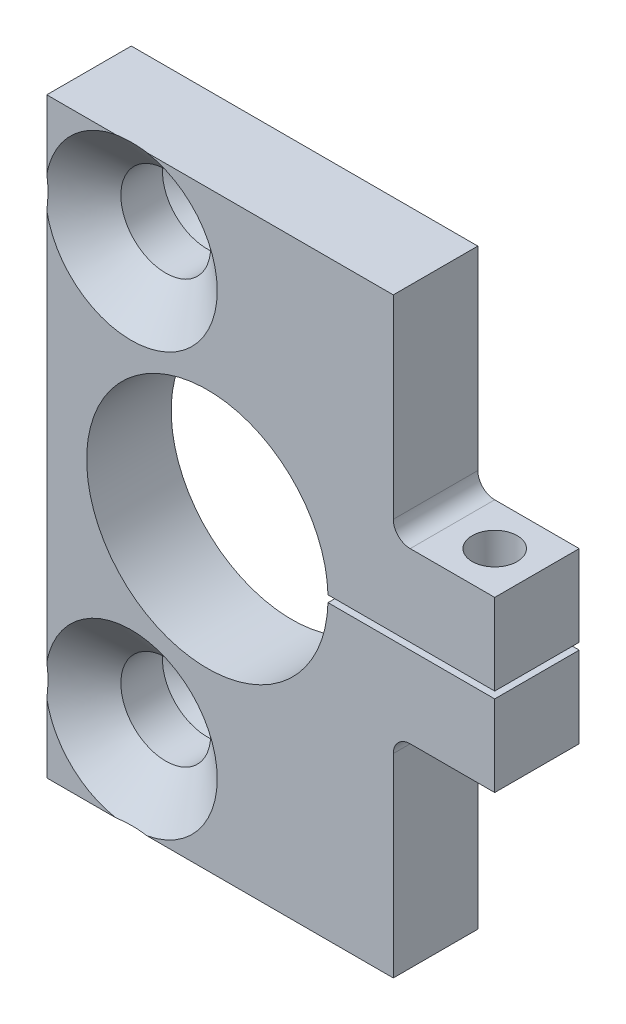
SolidWorks part; units mm, degrees
material "6061-T6 (SS)"
ref_plane "Front Plane" through (0, 0, 0) normal (0, 0, 1) x (1, 0, 0)
ref_plane "Top Plane" through (0, 0, 0) normal (0, 1, 0) x (1, 0, 0)
ref_plane "Right Plane" through (0, 0, 0) normal (1, 0, 0) x (0, 0, -1)
sketch "Sketch1" plane through (0, 0, 0) normal (0, 0, 1) x (1, 0, 0)
  line L1 (-33.655, -44.45) -> (33.655, -44.45)
  line L2 (-33.655, -44.45) -> (-33.655, 44.45)
  line L3 (-33.655, 44.45) -> (33.655, 44.45)
  line L4 (33.655, -44.45) -> (33.655, 44.45)
  line L5 (-33.655, -44.45) -> (33.655, 44.45) construction
  line L6 (-33.655, 44.45) -> (33.655, -44.45) construction
  point P0 (0, 0)
  dimension "D1" = 67.31
  dimension "D2" = 88.9
extrude "Extrude1" add sketch "Sketch1" along normal blind 12.7
sketch "Sketch2" plane through (0, 0, 12.7) normal (0, 0, 1) x (1, 0, 0)
  line L0 (-9.525, 0) -> (-33.655, 0) construction
  line L5 (-33.655, 44.45) -> (-33.655, -44.45) construction
  circle A0 centre (-9.525, 0) radius 18.1356
  dimension "D1" = 36.2712
  dimension "D2" = 24.13
extrude "Extrude2" cut sketch "Sketch2" against normal through all
sketch "Sketch3" plane through (0, 0, 12.7) normal (0, 0, 1) x (1, 0, 0)
  line L0 (8.6106, 0) -> (33.655, 0) construction
  line L1 (33.655, -44.45) -> (33.655, 44.45) construction
  line L3 (6.8985, -0.508) -> (35.3671, -0.508)
  line L4 (6.8985, -0.508) -> (6.8985, 0.508)
  line L5 (6.8985, 0.508) -> (35.3671, 0.508)
  line L6 (35.3671, -0.508) -> (35.3671, 0.508)
  line L7 (6.8985, -0.508) -> (35.3671, 0.508) construction
  line L8 (6.8985, 0.508) -> (35.3671, -0.508) construction
  circle A0 centre (-9.525, 0) radius 18.1356 construction
  point P6 (21.1328, 0)
  dimension "D1" = 1.016
extrude "Extrude3" cut sketch "Sketch3" against normal through all
sketch "Sketch4" plane through (0, 44.45, 0) normal (0, 1, 0) x (1, 0, 0)
  line L0 (33.655, -6.35) -> (27.305, -6.35) construction
  line L1 (33.655, -12.7) -> (33.655, 0) construction
  dimension "D1" = 6.35
hole_wizard "1/4 Clearance Hole1" positions "3DSketch1" profile "Sketch5" hole size "1/4" standard "Ansi Inch" end condition through all
sketch3d "3DSketch1"
  point P0 (27.305, 44.45, 6.35)
sketch "Sketch5" plane through (27.305, 44.45, 6.35) normal (1, 0, 0) x (0, 0, 1)
  line L0 (0, 0) -> (0, 88.9)
  line L1 (0, 88.9) -> (3.3782, 88.9)
  line L2 (3.3782, 88.9) -> (3.3782, 0)
  line L5 (3.3782, 0) -> (0, 0)
  line L11 (0, -6.35) -> (0, 107.95) construction
  dimension "Thru Hole Dia." = 6.7564
  dimension "Thru Hole Depth" = 88.9
sketch "Sketch6" plane through (0, -44.45, 0) normal (0, -1, 0) x (1, 0, 0)
  line L0 (-33.655, 6.35) -> (-27.305, 6.35) construction
  line L1 (-33.655, 12.7) -> (-33.655, 0) construction
  dimension "D1" = 6.35
hole_wizard "Tap Drill for 1/4-20 Tap1" positions "3DSketch2" profile "Sketch7" hole size "1/4-20" standard "Ansi Inch"
sketch3d "3DSketch2"
  point P0 (-31.75, -38.1, 4.7625)
sketch "Sketch7" plane through (-31.75, -38.1, 4.7625) normal (1, 0, 0) x (0, 0, -1)
  line L0 (0, 0) -> (0, 19.3138)
  line L1 (0, 19.3138) -> (2.5527, 17.78)
  line L2 (2.5527, 17.78) -> (2.5527, 0)
  line L5 (2.5527, 0) -> (0, 0)
  line L10 (0, 19.3138) -> (-2.5527, 17.78) construction
  line L11 (0, -6.35) -> (0, 107.95) construction
  dimension "Hole Dia." = 5.1054
  dimension "Hole Depth" = 17.78
  dimension "Drill Angle" = 118
sketch "Sketch8" plane through (0, 0, 12.7) normal (0, 0, 1) x (1, 0, 0)
  line L0 (-33.655, 31.75) -> (-20.955, 31.75) construction
  line L1 (-33.655, 44.45) -> (-33.655, -44.45) construction
  line L2 (33.655, 44.45) -> (-33.655, 44.45) construction
  dimension "D1" = 12.7
  dimension "D2" = 12.7
hole_wizard "CSK for 1/2 Flat Head Machine Screw (100)1" positions "3DSketch3" profile "Sketch9" countersink size "1/2" standard "Ansi Inch"
sketch3d "3DSketch3"
  point P0 (-20.955, 31.75, 12.7)
sketch "Sketch9" plane through (-20.955, 31.75, 12.7) normal (1, 0, 0) x (0, -1, 0)
  line L0 (0, 0) -> (0, 15.4835)
  line L1 (0, 15.4835) -> (6.7462, 11.43)
  line L2 (6.7462, 11.43) -> (6.7462, 5.177)
  line L3 (6.7462, 5.177) -> (12.9159, 0)
  line L5 (12.9159, 0) -> (0, 0)
  line L6 (-6.7462, 5.177) -> (-12.9159, 0) construction
  line L10 (0, 15.4835) -> (-6.7462, 11.43) construction
  line L11 (0, -6.35) -> (0, 107.95) construction
  dimension "Hole Dia." = 13.4925
  dimension "Hole Depth" = 11.43
  dimension "Near C'Sink Dia." = 25.8318
  dimension "Near C'Sink Angle" = 100
  dimension "Drill Angle" = 118
mirror "Mirror1" about plane through (0, 0, 0) normal (0, 1, 0) of "CSK for 1/2 Flat Head Machine Screw (100)1"
sketch "Sketch10" plane through (0, 0, 12.7) normal (0, 0, 1) x (1, 0, 0)
  line L1 (33.655, 44.45) -> (18.415, 44.45)
  line L2 (33.655, 44.45) -> (33.655, 12.7)
  line L3 (33.655, 12.7) -> (18.415, 12.7)
  line L4 (18.415, 44.45) -> (18.415, 12.7)
  dimension "D1" = 15.24
  dimension "D2" = 31.75
extrude "Extrude4" cut sketch "Sketch10" against normal through all
fillet "Fillet1" radius 2.54 1 edges at (18.415, 12.7, 6.35)
mirror "Mirror2" about plane through (0, 0, 0) normal (0, 1, 0) of "Fillet1", "Extrude4"
